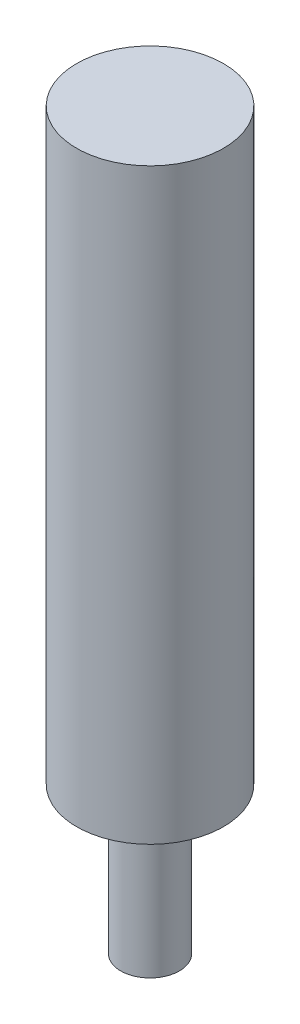
SolidWorks part; units mm, degrees
ref_plane "Alzado" through (0, 0, 0) normal (0, 0, 1) x (1, 0, 0)
ref_plane "Planta" through (0, 0, 0) normal (0, 1, 0) x (1, 0, 0)
ref_plane "Vista lateral" through (0, 0, 0) normal (1, 0, 0) x (0, 0, -1)
sketch "Sketch1" plane through (0, 0, 0) normal (0, 0, 1) x (1, 0, 0)
  line L0 (0, 0) -> (5, 0)
  line L1 (5, 0) -> (5, -40)
  line L2 (5, -40) -> (2, -40)
  line L3 (2, -40) -> (2, -50)
  line L4 (2, -50) -> (0, -50)
  line L5 (0, -50) -> (0, 0)
  line L6 (0, -54) -> (0, 4) construction
revolve "Cuerpo" add sketch "Sketch1" angle 360 about L6
